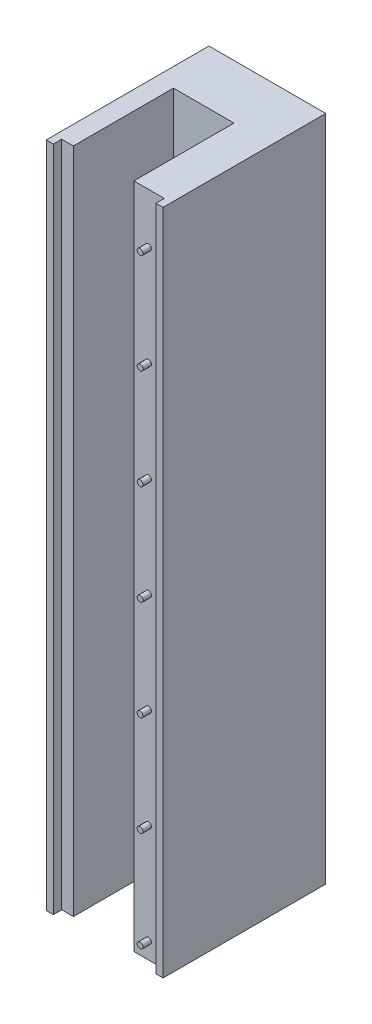
SolidWorks part; units mm, degrees
ref_plane "Top" through (0, 0, 0) normal (0, 0, 1) x (1, 0, 0)
ref_plane "Front" through (0, 0, 0) normal (0, 1, 0) x (1, 0, 0)
ref_plane "Right" through (0, 0, 0) normal (1, 0, 0) x (0, 0, -1)
sketch "Profile Sketch" plane through (0.0456, 0, -0.0242) normal (0, 1, 0) x (-1, 0, 0)
  line L0 (3.5456, -11.9758) -> (3.5456, 0.0242)
  line L1 (3.5456, 0.0242) -> (-0.1044, 0.0242)
  line L2 (-0.9544, 1.0242) -> (-0.9544, -18.4758)
  line L3 (-0.9544, -18.4758) -> (13.0456, -18.4758)
  line L4 (3.5456, -11.9758) -> (10.7956, -11.9758)
  line L5 (13.0456, -18.4758) -> (13.0456, 1.0242)
  line L6 (12.1956, 0.0242) -> (10.7956, 0.0242)
  line L7 (10.7956, 0.0242) -> (10.7956, -11.9758)
  line L8 (-0.1044, 0.0242) -> (-0.1044, 1.0242)
  line L9 (-0.9544, 1.0242) -> (-0.1044, 1.0242)
  line L10 (12.1956, 0.0242) -> (12.1956, 1.0242)
  line L11 (12.1956, 1.0242) -> (13.0456, 1.0242)
  line L12 (12.0456, 0.0242) -> (12.0456, 1.0242) construction
  dimension "Sprocket Height" = 1
  dimension "Tape Depth" = 12
  dimension "D8" = 0.15
  dimension "Reel Width" = 12
  dimension "Wall Thickness" = 1
  dimension "D1" = 18.5
  dimension "D2" = 3.5
  dimension "D3" = 1.25
  dimension "D5" = 7.25
  dimension "D4" = 0.15
extrude "Profile Extrude" add sketch "Profile Sketch" along normal blind 80
sketch "Sprocket Sketch" plane through (0, 0, 0) normal (0, 0, 1) x (1, 0, 0)
  line L0 (0.15, 80) -> (0.15, 0) construction
  circle A0 centre (-1.75, 2) radius 0.35
  dimension "D2" = 0.7
  dimension "D3" = 2
  dimension "D1" = 1.9
extrude "Sprocket Extrude" add sketch "Sprocket Sketch" along normal blind 1 contours A0
pattern_linear "Sprocket Pattern" count 7 spacing 12 along (0, 1, 0) of "Sprocket Extrude"
ref_plane "Mid Plane" through (0, 40, 0) normal (0, -1, 0) x (-1, 0, 0)
sketch "Magnet Hole Sketch" plane through (0, 0, -12) normal (0, 0, 1) x (1, 0, 0)
  line L0 (-7.125, 0) -> (-7.125, 10) construction
  line L1 (-10.75, 0) -> (-3.5, 0) construction
  line L2 (-7.125, 10) -> (-7.125, 13.5) construction
  line L3 (-7.125, 10) -> (-3.7963, 11.0816) construction
  circle A0 centre (-7.125, 10) radius 2.75 construction
  circle A1 centre (-7.125, 10) radius 4.75 construction
  arc A2 (-5.276, 12.9718) -> (-7.125, 13.5) centre (-6.0787, 13.6623) cw
  arc A3 (-5.276, 12.9718) -> (-3.7963, 11.0816) centre (-4.3484, 12.1737) cw
  circle A4 centre (-7.125, 10) radius 3.5 construction
  arc A5 (-3.7273, 9.1599) -> (-5.0678, 7.1684) centre (-4.1997, 8.031) cw
  arc A6 (-3.7273, 9.1599) -> (-3.7963, 11.0816) centre (-3.3186, 10.1366) cw
  arc A7 (-6.8741, 6.509) -> (-9.1822, 7.1684) centre (-8.0937, 6.6094) cw
  arc A8 (-6.8741, 6.509) -> (-5.0678, 7.1684) centre (-5.8188, 6.4222) cw
  arc A9 (-10.3676, 8.6826) -> (-10.4537, 11.0816) centre (-10.649, 9.8735) cw
  arc A10 (-10.3676, 8.6826) -> (-9.1822, 7.1684) centre (-10.1241, 7.6522) cw
  arc A11 (-9.3799, 12.6768) -> (-7.125, 13.5) centre (-8.3343, 13.3124) cw
  arc A12 (-9.3799, 12.6768) -> (-10.4537, 11.0816) centre (-10.2847, 12.1268) cw
  point P35 (-7.125, 10)
  dimension "D2" = 5.5
  dimension "D3" = 0.75
  dimension "D4" = 1.25
  dimension "D1" = 10
  dimension "D5" = 72
  dimension "D6" = 5
extrude "Magnet Cut" cut sketch "Magnet Hole Sketch" along normal blind 5 from surface at -6.5 starting at face at (-6, 40, -18.5)
chamfer "Magnet Chamfer" distance 0.75 angle 45 10 edges at (-8.7539, 14.462, -18.5) (-9.4063, 11.5356, -18.5) (-6.3696, 12.6442, -18.5) (-11.8719, 9.8296, -18.5) (-3.3848, 12.928, -18.5) (-9.2904, 8.3048, -18.5) (-4.3768, 10.0986, -18.5) (-8.4299, 5.4327, -18.5) (-3.1845, 7.3477, -18.5) (-6.1819, 7.4168, -18.5)
mirror "Magnet Mirror" about plane through (0, 40, 0) normal (0, -1, 0) of "Magnet Chamfer", "Magnet Cut"
equation "\"Tape Clearance\"= 0.15mm'0.15mm works for 0.4 mm nozzles on my printer."
equation "\"D8@Profile Sketch\"=\"Tape Clearance\""
equation "\"D2@Sprocket Sketch\"=1.50mm - 2* \"Sprocket Clearance\""
equation "\"Sprocket Clearance\"= 0.4mm'0.4mm works for 0.4 mm nozzles on my printer."
equation "\"D1@Sprocket Sketch\"=\"Tape Clearance\"+1.75"
equation "\"D4@Profile Sketch\"=\"Tape Clearance\""
